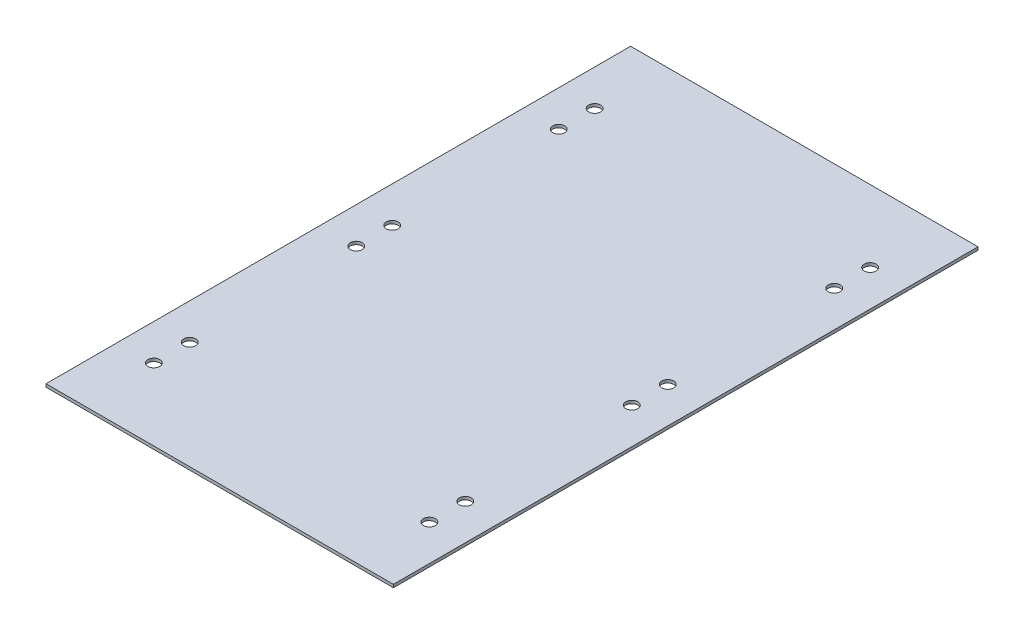
SolidWorks part; units mm, degrees
ref_plane "Front Plane" through (0, 0, 0) normal (0, 0, 1) x (1, 0, 0)
ref_plane "Top Plane" through (0, 0, 0) normal (0, 1, 0) x (1, 0, 0)
ref_plane "Right Plane" through (0, 0, 0) normal (1, 0, 0) x (0, 0, -1)
sketch "Sketch1" plane through (0, 0, 0) normal (0, 1, 0) x (1, 0, 0)
  line L0 (-92.075, 0) -> (92.075, 0) construction
  line L1 (-92.075, -154.94) -> (92.075, -154.94)
  line L2 (-92.075, -154.94) -> (-92.075, 154.94)
  line L3 (-92.075, 154.94) -> (92.075, 154.94)
  line L4 (92.075, -154.94) -> (92.075, 154.94)
  line L5 (0, 154.94) -> (0, -154.94) construction
  dimension "D1" = 309.88
  dimension "D2" = 184.15
extrude "Boss-Extrude1" add sketch "Sketch1" along normal blind 1.5875
sketch "Sketch2" plane through (0, 1.5875, 0) normal (0, 1, 0) x (1, 0, 0)
  line L0 (-92.075, 154.94) -> (-92.075, -154.94) construction
  line L1 (92.075, 154.94) -> (-92.075, 154.94) construction
  line L2 (-92.075, -154.94) -> (92.075, -154.94) construction
  line L3 (-92.075, 0) -> (92.075, 0) construction
  line L4 (92.075, -154.94) -> (92.075, 154.94) construction
  line L5 (-73.025, -9.525) -> (-73.025, 9.525) construction
  line L6 (-73.025, 116.84) -> (-73.025, -116.84) construction
  circle A0 centre (-73.025, 9.525) radius 3.175
  circle A1 centre (-73.025, -9.525) radius 3.175
  circle A2 centre (-73.025, 116.84) radius 3.175
  circle A3 centre (-73.025, 97.79) radius 3.175
  circle A4 centre (-73.025, -116.84) radius 3.175
  circle A5 centre (-73.025, -97.79) radius 3.175
  point P22 (-73.025, 0)
  dimension "D1" = 6.35
  dimension "D2" = 19.05
  dimension "D3" = 19.05
  dimension "D4" = 19.05
  dimension "D5" = 19.05
  dimension "D6" = 38.1
  dimension "D7" = 38.1
extrude "Cut-Extrude1" cut sketch "Sketch2" against normal through all
mirror "Mirror1" about plane through (0, 0, 0) normal (1, 0, 0) of "Cut-Extrude1"
ref_plane "Plane1" through (0, 0, 59.69) normal (0, 0, 1) x (1, 0, 0)
